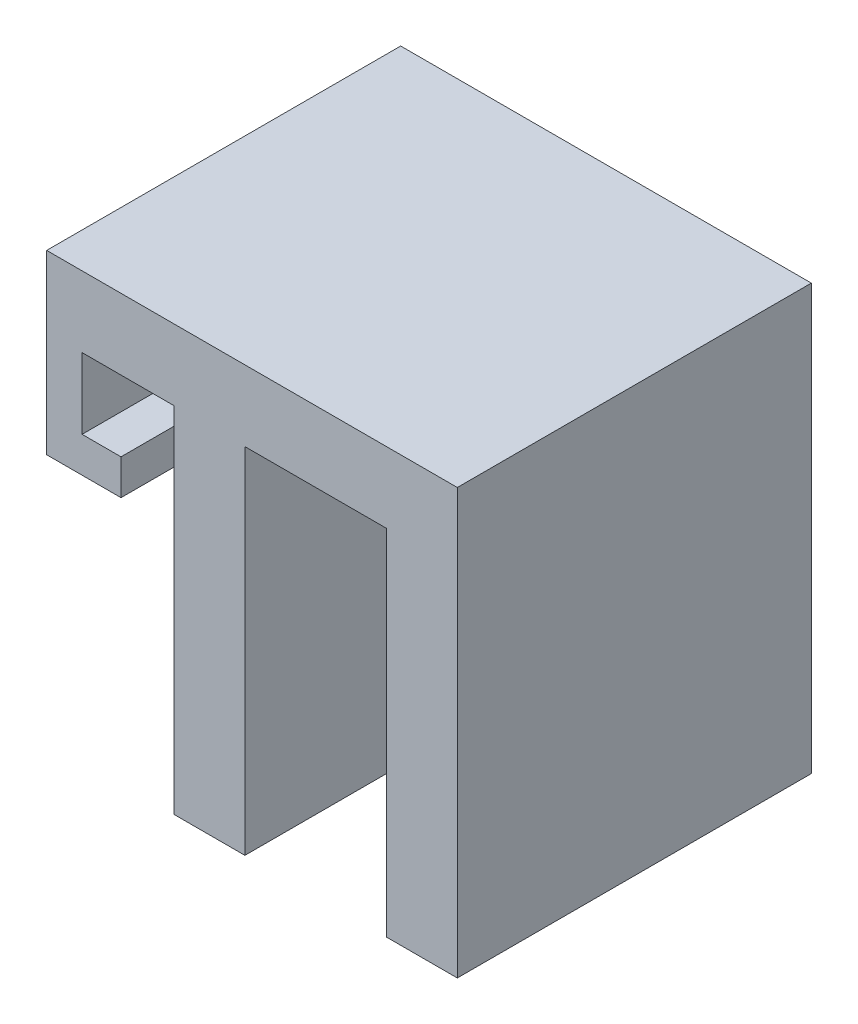
SolidWorks part; units mm, degrees
ref_plane "Front Plane" through (0, 0, 0) normal (0, 0, 1) x (1, 0, 0)
ref_plane "Top Plane" through (0, 0, 0) normal (0, 1, 0) x (1, 0, 0)
ref_plane "Right Plane" through (0, 0, 0) normal (1, 0, 0) x (0, 0, -1)
sketch "Sketch1" plane through (0, 0, 0) normal (0, 0, 1) x (1, 0, 0)
  line L0 (0, 0) -> (45.9503, 0) construction
  line L1 (0, 0) -> (0, -43.168) construction
  line L2 (-4, 0) -> (-4, -43.168) construction
  line L3 (-4, -10) -> (-4, 0)
  line L4 (-4, 0) -> (0, 0)
  line L5 (0, 0) -> (0, -10)
  line L6 (0, -10) -> (2, -10)
  line L7 (2, -10) -> (2, 2)
  line L8 (2, 2) -> (-5, 2)
  line L9 (-6, 0) -> (-6, -10)
  line L10 (-6, -10) -> (-4, -10)
  line L11 (-8, 2) -> (-9.6, 2)
  line L12 (-5, 2) -> (-8, 2)
  line L14 (-6, 0) -> (-7, 0)
  line L24 (-9.6, 2) -> (-9.6, -3)
  line L25 (-9.6, -3) -> (-7.5, -3)
  line L26 (-7.5, -3) -> (-7.5, -2)
  line L27 (-7.5, -2) -> (-8.6, -2)
  line L28 (-8.6, -2) -> (-8.6, 0)
  line L29 (-8.6, 0) -> (-7, 0)
  dimension "D2" = 2
  dimension "D3" = 2
  dimension "D4" = 2
  dimension "D5" = 10
  dimension "D6" = 10
  dimension "D7" = 2.6
  dimension "D8" = 2
  dimension "D9" = 2
  dimension "D10" = 1
  dimension "D11" = 1.5
  dimension "D12" = 1
  dimension "D1" = 4
extrude "Boss-Extrude1" add sketch "Sketch1" along normal blind 10
